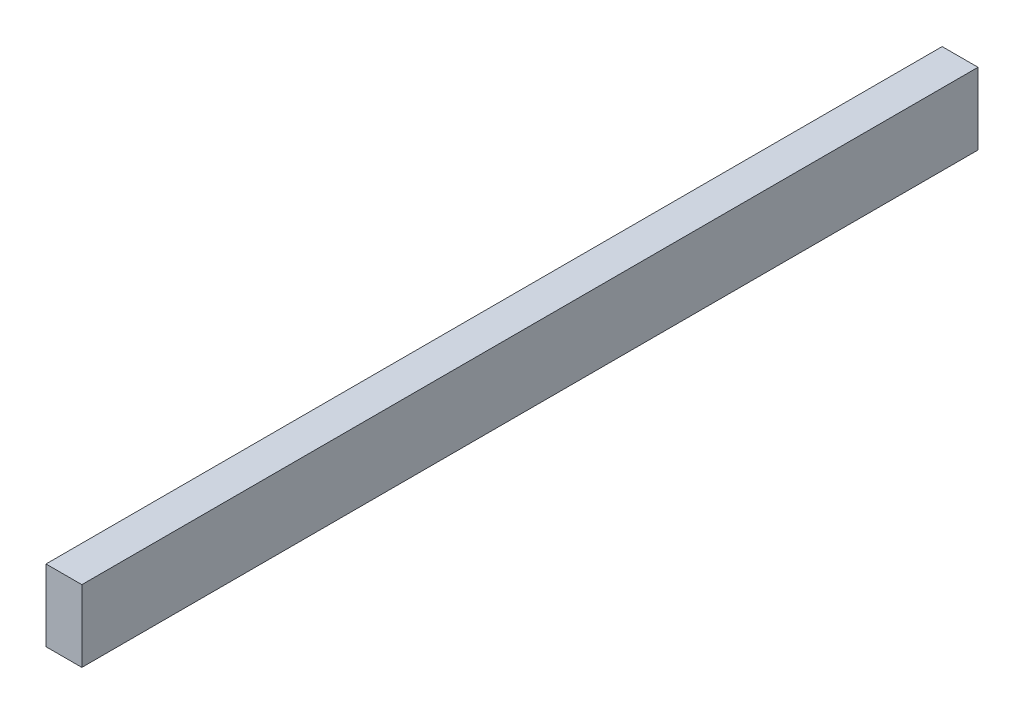
SolidWorks part; units mm, degrees
ref_plane "前视基准面" through (0, 0, 0) normal (0, 0, 1) x (1, 0, 0)
ref_plane "上视基准面" through (0, 0, 0) normal (0, 1, 0) x (1, 0, 0)
ref_plane "右视基准面" through (0, 0, 0) normal (1, 0, 0) x (0, 0, -1)
sketch "草图1" plane through (0, 0, 0) normal (0, 0, 1) x (1, 0, 0)
  line L1 (20, -40) -> (-20, -40)
  line L2 (20, -40) -> (20, 40)
  line L3 (20, 40) -> (-20, 40)
  line L4 (-20, -40) -> (-20, 40)
  line L5 (20, -40) -> (-20, 40) construction
  line L6 (20, 40) -> (-20, -40) construction
  point P0 (0, 0)
  dimension "D1" = 40
  dimension "D2" = 80
extrude "凸台-拉伸1" add sketch "草图1" along normal blind 1000
